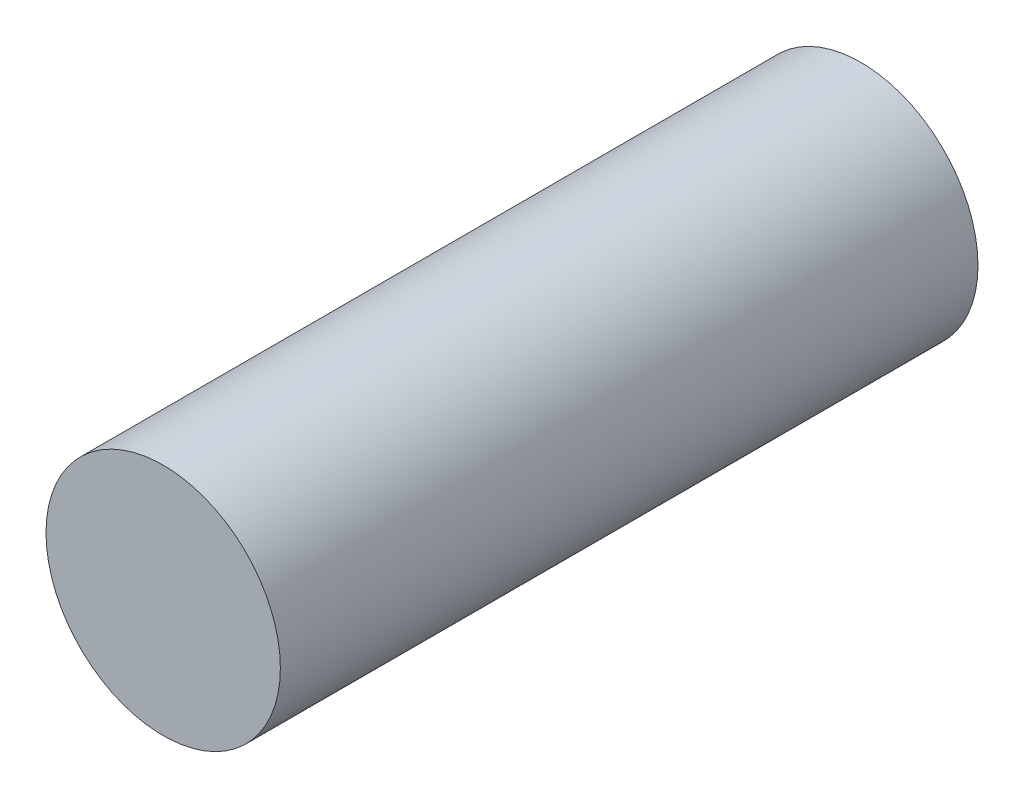
SolidWorks part; units mm, degrees
ref_plane "Plan de face" through (0, 0, 0) normal (0, 0, 1) x (1, 0, 0)
ref_plane "Plan de dessus" through (0, 0, 0) normal (0, 1, 0) x (1, 0, 0)
ref_plane "Plan de droite" through (0, 0, 0) normal (1, 0, 0) x (0, 0, -1)
sketch "Esquisse1" plane through (0, 0, 0) normal (0, 0, 1) x (1, 0, 0)
  circle A0 centre (0, 0) radius 3
  dimension "D1" = 6
extrude "Boss.-Extru.1" add sketch "Esquisse1" along normal blind 17.86
